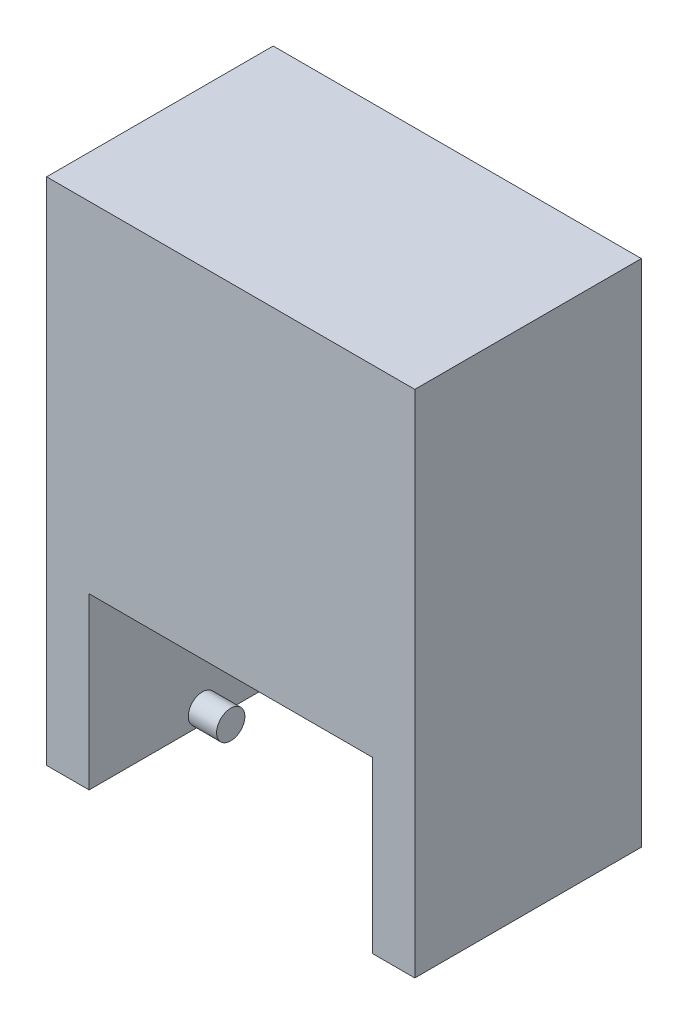
SolidWorks part; units mm, degrees
ref_plane "Front Plane" through (0, 0, 0) normal (0, 0, 1) x (1, 0, 0)
ref_plane "Top Plane" through (0, 0, 0) normal (0, 1, 0) x (1, 0, 0)
ref_plane "Right Plane" through (0, 0, 0) normal (1, 0, 0) x (0, 0, -1)
other "Center of Mass"
sketch "Sketch1" plane through (0, 0, 0) normal (0, 0, 1) x (1, 0, 0)
  line L1 (0, 0) -> (330.2, 0)
  line L2 (0, 0) -> (0, 457.2)
  line L3 (0, 457.2) -> (330.2, 457.2)
  line L4 (330.2, 0) -> (330.2, 457.2)
  dimension "D1" = 330.2
  dimension "D2" = 457.2
extrude "Boss-Extrude1" add sketch "Sketch1" along normal blind 203.2
sketch "Sketch2" plane through (0, 0, 203.2) normal (0, 0, 1) x (1, 0, 0)
  line L0 (0, 0) -> (330.2, 0) construction
  line L1 (38.1, 0) -> (292.1, 0)
  line L2 (38.1, 0) -> (38.1, 152.4)
  line L3 (38.1, 152.4) -> (292.1, 152.4)
  line L4 (292.1, 0) -> (292.1, 152.4)
  line L6 (165.1, 181.2807) -> (165.1, 71.8759) construction
  line L7 (0, 457.2) -> (0, 0) construction
  dimension "D1" = 165.1
  dimension "D2" = 254
  dimension "D3" = 152.4
extrude "Cut-Extrude1" cut sketch "Sketch2" against normal blind 294.386 and the other way blind 115.316
sketch "Sketch3" plane through (292.1, 0, 0) normal (-1, 0, 0) x (0, 0, 1)
  line L0 (203.2, 0) -> (0, 0) construction
  line L1 (203.2, 457.2) -> (203.2, 0) construction
  circle A0 centre (101.6, 12.7) radius 12.7
  dimension "D1" = 25.4
  dimension "D2" = 12.7
  dimension "D3" = 101.6
extrude "Boss-Extrude2" add sketch "Sketch3" along normal blind 25.4
ref_plane "Plane1" through (165.1, 0, 0) normal (-1, 0, 0) x (0, 0, 1)
mirror "Mirror1" about plane through (165.1, 0, 0) normal (-1, 0, 0) of "Boss-Extrude2"
other "Center of Mass Reference Point1"
ref_plane "Plane2" through (0, 0, 101.6) normal (0, 0, 1) x (1, 0, 0)
